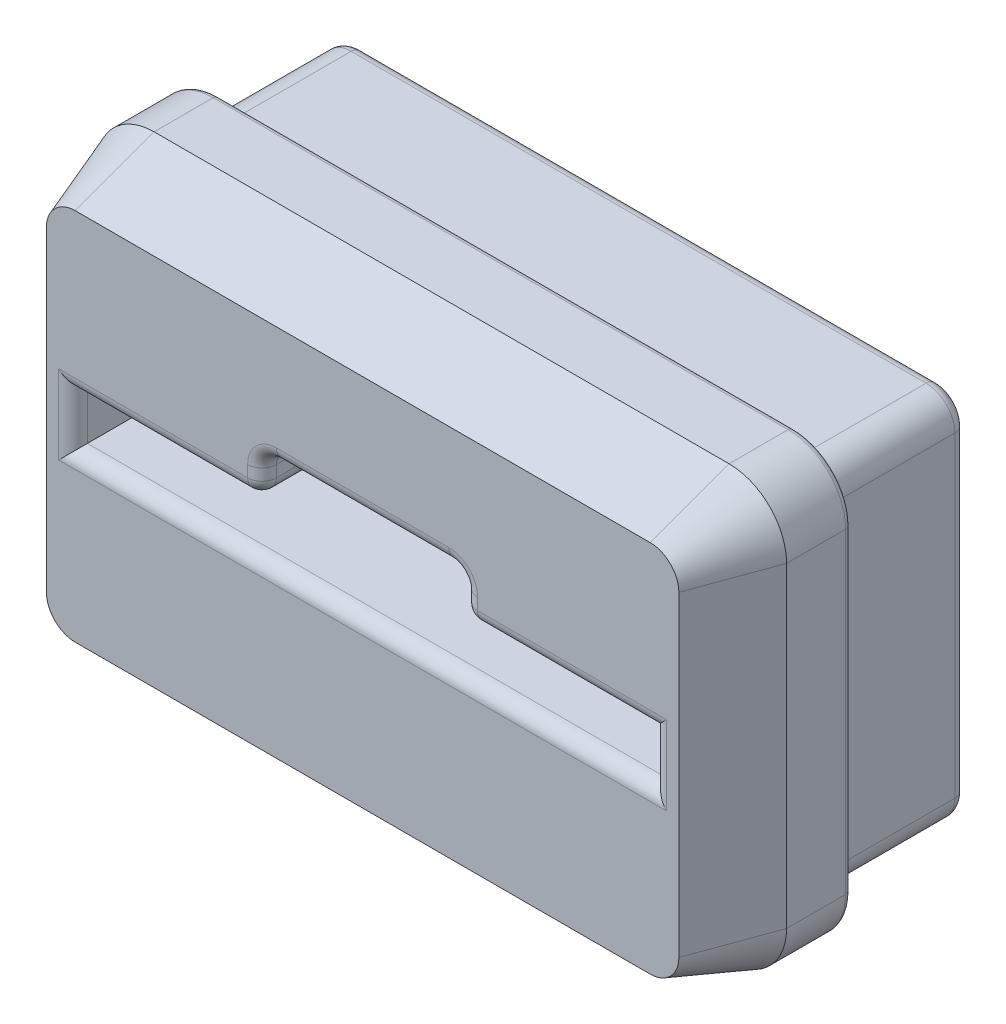
SolidWorks part; units mm, degrees
ref_plane "Front Plane" through (0, 0, 0) normal (0, 0, 1) x (1, 0, 0)
ref_plane "Top Plane" through (0, 0, 0) normal (0, 1, 0) x (1, 0, 0)
ref_plane "Right Plane" through (0, 0, 0) normal (1, 0, 0) x (0, 0, -1)
sketch "Sketch1" plane through (0, 0, 0) normal (0, 1, 0) x (1, 0, 0)
  line L1 (-12, 6.5) -> (12, 6.5)
  line L2 (-12, 6.5) -> (-12, -6.5)
  line L3 (-12, -6.5) -> (12, -6.5)
  line L4 (12, 6.5) -> (12, -6.5)
  line L5 (-12, 6.5) -> (12, -6.5) construction
  line L6 (-12, -6.5) -> (12, 6.5) construction
  point P0 (0, 0)
  dimension "D1" = 24
  dimension "D2" = 13
extrude "Boss-Extrude1" add sketch "Sketch1" along normal blind 15
sketch "Sketch2" plane through (0, 0, 6.5) normal (0, 0, 1) x (1, 0, 0)
  line L0 (0, 0) -> (0, 15) construction
  line L1 (-12, 15) -> (12, 15) construction
  line L2 (-12, 0) -> (12, 0) construction
  line L3 (-10.075, 8.45) -> (10.075, 8.45)
  line L4 (-10.075, 8.45) -> (-10.075, 6.7)
  line L5 (-10.075, 6.7) -> (10.075, 6.7)
  line L6 (10.075, 8.45) -> (10.075, 6.7)
  line L7 (-10.075, 8.45) -> (10.075, 6.7) construction
  line L8 (-10.075, 6.7) -> (10.075, 8.45) construction
  point P5 (0, 7.575)
  dimension "D1" = 6.7
  dimension "D2" = 1.75
  dimension "D3" = 20.15
extrude "Cut-Extrude1" cut sketch "Sketch2" against normal blind 15
fillet "Fillet1" radius 2 4 edges at (12, 15, 0) (12, 0, 0) (-12, 0, 0) (-12, 15, 0)
chamfer "Chamfer2" distance 1 angle 70 8 edges at (0, 0, 6.5) (-11.4142, 0.5858, 6.5) (11.4142, 0.5858, 6.5) (-12, 7.5, 6.5) (12, 7.5, 6.5) (-11.4142, 14.4142, 6.5) (11.4142, 14.4142, 6.5) (0, 15, 6.5)
fillet "Fillet2" radius 0.5 4 edges at (10.075, 7.575, 6.5) (0, 8.45, 6.5) (-10.075, 7.575, 6.5) (0, 6.7, 6.5)
sketch "Sketch4" plane through (0, 0, -6.5) normal (0, 0, -1) x (-1, 0, 0)
  line L0 (-10.075, 8.45) -> (-8.575, 8.45)
  line L1 (-10.075, 6.7) -> (10.075, 6.7)
  line L2 (-10.075, 6.7) -> (-10.075, 8.45)
  line L3 (-8.575, 11.8912) -> (8.575, 11.8912)
  line L4 (10.075, 6.7) -> (10.075, 8.45)
  line L5 (-10.075, 8.45) -> (10.075, 8.45) construction
  line L6 (-8.575, 8.45) -> (-8.575, 11.8912)
  line L7 (10.075, 8.45) -> (8.575, 8.45)
  line L8 (8.575, 8.45) -> (8.575, 11.8912)
  dimension "D2" = 1.5
  dimension "D3" = 1.5
extrude "Cut-Extrude4" cut sketch "Sketch4" against normal blind 11
sketch "Sketch5" plane through (0, 0, -6.5) normal (0, 0, -1) x (-1, 0, 0)
  line L5 (-13.5112, 17.4159) -> (13.3444, 17.4159)
  line L6 (-13.5112, 17.4159) -> (-13.5112, -1.8918)
  line L7 (-13.5112, -1.8918) -> (13.3444, -1.8918)
  line L8 (10, 14) -> (-10, 14)
  line L9 (-11, 13) -> (-11, 2)
  line L10 (-10, 1) -> (10, 1)
  line L11 (11, 2) -> (11, 13)
  line L12 (10, 14) -> (-10, 14)
  line L13 (-11, 13) -> (-11, 2)
  line L14 (-10, 1) -> (10, 1)
  line L15 (11, 2) -> (11, 13)
  line L16 (13.3444, 17.4159) -> (13.3444, -1.8918)
  arc A8 (-10, 14) -> (-11, 13) centre (-10, 13) ccw
  arc A9 (-11, 2) -> (-10, 1) centre (-10, 2) ccw
  arc A10 (10, 1) -> (11, 2) centre (10, 2) ccw
  arc A11 (11, 13) -> (10, 14) centre (10, 13) ccw
  arc A12 (-10, 14) -> (-11, 13) centre (-10, 13) ccw
  arc A13 (-11, 2) -> (-10, 1) centre (-10, 2) ccw
  arc A14 (10, 1) -> (11, 2) centre (10, 2) ccw
  arc A15 (11, 13) -> (10, 14) centre (10, 13) ccw
  dimension "D1" = 1
extrude "Cut-Extrude5" cut sketch "Sketch5" against normal blind 8
sketch "Sketch6" plane through (0, 0, -6.5) normal (0, 0, -1) x (-1, 0, 0)
  line L8 (-9, 5.7) -> (9, 5.7)
  line L9 (10.075, 6.7) -> (-10.075, 6.7) construction
  line L12 (10, 13) -> (-10, 13)
  line L13 (-10, 13) -> (-10, 2)
  line L14 (-10, 2) -> (10, 2)
  line L15 (10, 2) -> (10, 13)
  line L17 (-10, 4.7) -> (-10, 3)
  line L18 (-9, 2) -> (9, 2)
  line L19 (10, 3) -> (10, 4.7)
  arc A8 (9, 2) -> (10, 3) centre (9, 3) ccw
  arc A9 (9, 5.7) -> (10, 4.7) centre (9, 4.7) cw
  arc A10 (-10, 3) -> (-9, 2) centre (-9, 3) ccw
  arc A11 (-9, 5.7) -> (-10, 4.7) centre (-9, 4.7) ccw
  dimension "D3" = 1
  dimension "D2" = 1
  dimension "D1" = 1
extrude "Cut-Extrude6" cut sketch "Sketch6" against normal blind 11
sketch "Sketch7" plane through (0, 0, -6.5) normal (0, 0, -1) x (-1, 0, 0)
  line L1 (-14.3755, 18.0591) -> (15.6072, 18.0591)
  line L2 (-14.3755, 18.0591) -> (-14.3755, -3.4999)
  line L3 (-14.3755, -3.4999) -> (15.6072, -3.4999)
  line L4 (15.6072, 18.0591) -> (15.6072, -3.4999)
extrude "Cut-Extrude7" cut sketch "Sketch7" against normal blind 3
chamfer "Chamfer3" distance 2 angle 45 2 edges at (9.325, 8.45, -3.5) (-9.325, 8.45, -3.5)
fillet "Fillet3" radius 0.4 22 edges at (-9.7071, 5.4071, -3.5) (0, 5.7, -3.5) (9.7071, 5.4071, -3.5) (10, 3.85, -3.5) (9.7071, 2.2929, -3.5) (0, 2, -3.5) (-9.7071, 2.2929, -3.5) (10.7071, 13.7071, -3.5) (11, 7.5, -3.5) (10.7071, 1.2929, -3.5) (0, 1, -3.5) (-10.7071, 1.2929, -3.5) (-11, 7.5, -3.5) (-10.7071, 13.7071, -3.5) (9.325, 10.45, -3.5) (8.575, 11.1706, -3.5) (-9.325, 10.45, -3.5) (-8.575, 11.1706, -3.5) (0, 11.8912, -3.5) (0, 6.7, -3.5) (-10, 3.85, -3.5) (0, 14, -3.5)
fillet "Fillet4" radius 0.2 8 edges at (0, 15, 1.5) (11.4142, 14.4142, 1.5) (12, 7.5, 1.5) (11.4142, 0.5858, 1.5) (0, 0, 1.5) (-11.4142, 0.5858, 1.5) (-12, 7.5, 1.5) (-11.4142, 14.4142, 1.5)
sketch "Sketch8" plane through (0, 0, 4.5) normal (0, 0, -1) x (-1, 0, 0)
  line L0 (8.575, 8.45) -> (-8.575, 8.45) construction
  line L1 (-3.5, 9.85) -> (3.5, 9.85)
  line L2 (-3.5, 9.85) -> (-3.5, 7.05)
  line L3 (-3.5, 7.05) -> (3.5, 7.05)
  line L4 (3.5, 9.85) -> (3.5, 7.05)
  line L5 (-3.5, 9.85) -> (3.5, 7.05) construction
  line L6 (-3.5, 7.05) -> (3.5, 9.85) construction
  point P0 (0, 8.45)
  dimension "D1" = 2.8
  dimension "D2" = 7
extrude "Cut-Extrude8" cut sketch "Sketch8" against normal through all
fillet "Fillet5" radius 0.5 9 edges at (3.5, 8.45, 5.25) (3.5, 8.5964, 6.3536) (3.5, 9.4, 6.5) (0, 9.85, 6.5) (-3.5, 9.4, 6.5) (-3.5, 8.45, 5.25) (-3.5, 8.5964, 6.3536) (-3.5, 9.85, 5.5) (3.5, 9.85, 5.5)
